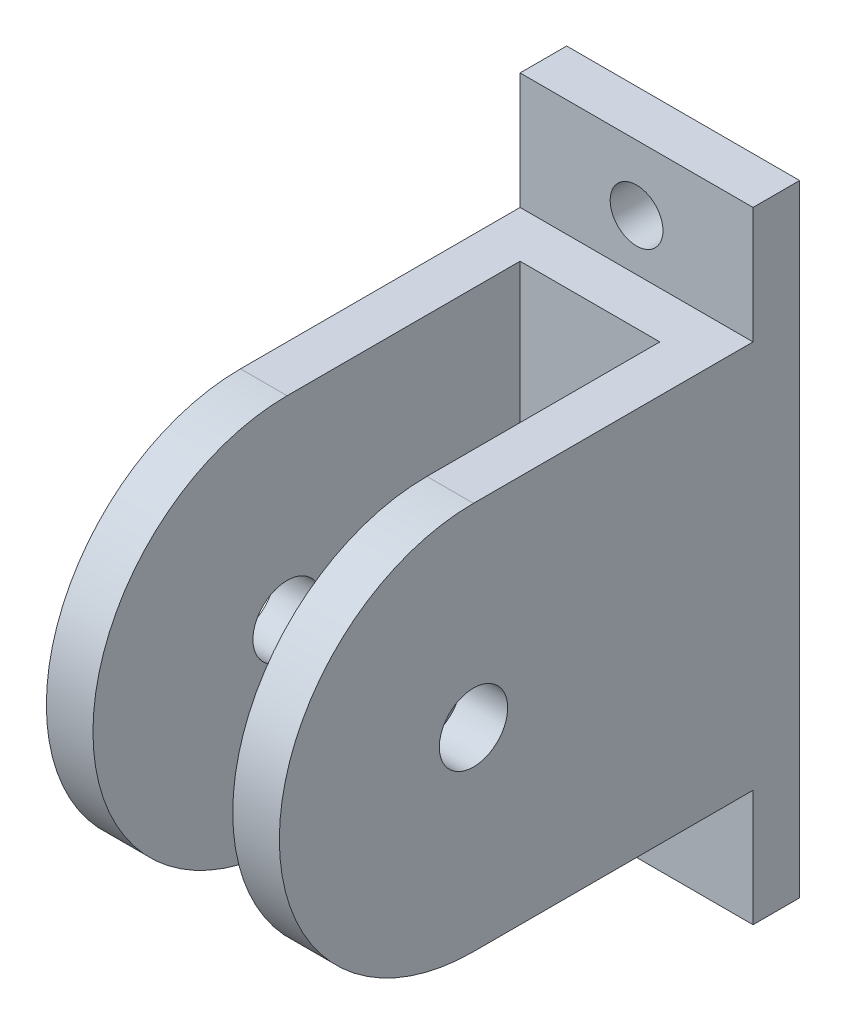
SolidWorks part; units mm, degrees
ref_plane "Piano frontale" through (0, 0, 0) normal (0, 0, 1) x (1, 0, 0)
ref_plane "Piano superiore" through (0, 0, 0) normal (0, 1, 0) x (1, 0, 0)
ref_plane "Piano destro" through (0, 0, 0) normal (1, 0, 0) x (0, 0, -1)
sketch "Schizzo1" plane through (0, 0, 0) normal (0, 0, 1) x (1, 0, 0)
  line L1 (-10, 20) -> (5, 20)
  line L2 (-10, 20) -> (-10, -20)
  line L3 (-10, -20) -> (5, -20)
  line L4 (5, 20) -> (5, -20)
  dimension "D1" = 40
  dimension "D2" = 15
extrude "Estrusione-Estrusione1" add sketch "Schizzo1" along normal blind 3
sketch "Schizzo2" plane through (0, 0, 3) normal (0, 0, 1) x (1, 0, 0)
  line L1 (-10, 12.5) -> (5, 12.5)
  line L2 (-10, 12.5) -> (-10, -12.5)
  line L3 (-10, -12.5) -> (5, -12.5)
  line L4 (5, 12.5) -> (5, -12.5)
  dimension "D1" = 25
  dimension "D2" = 15
extrude "Estrusione-Estrusione2" add sketch "Schizzo2" along normal blind 3
sketch "Schizzo5" plane through (-10, 0, 0) normal (-1, 0, 0) x (0, 0, 1)
  line L0 (6, 12.5) -> (21, 12.5)
  line L1 (6, 12.5) -> (6, -12.5)
  line L2 (6, -12.5) -> (21, -12.5)
  arc A0 (21, 12.5) -> (21, -12.5) centre (21, 0) cw
  point P7 (33.5, 0)
  dimension "D1" = 15
extrude "Estrusione-Estrusione4" add sketch "Schizzo5" against normal blind 3
sketch "Schizzo6" plane through (5, 0, 0) normal (1, 0, 0) x (0, 0, -1)
  line L0 (-6, -12.5) -> (-6, 12.5)
  line L1 (-6, 12.5) -> (-21, 12.5)
  line L2 (-6, -12.5) -> (-21, -12.5)
  arc A0 (-21, 12.5) -> (-21, -12.5) centre (-21, 0) ccw
extrude "Estrusione-Estrusione5" add sketch "Schizzo6" against normal blind 3
sketch "Schizzo7" plane through (-10, 0, 0) normal (-1, 0, 0) x (0, 0, 1)
  circle A0 centre (21, 0) radius 2.2
  point P0 (21, 0)
  dimension "D1" = 4.4
extrude "Taglio-Estrusione1" cut sketch "Schizzo7" against normal through all both and the other way through all
sketch "Schizzo9" plane through (0, 0, 0) normal (0, 0, -1) x (-1, 0, 0)
  line L0 (-5, 20) -> (10, 20) construction
  line L1 (-5, 0) -> (10, 0) construction
  line L2 (-5, -20) -> (-5, 20) construction
  line L3 (10, 20) -> (10, -20) construction
  circle A0 centre (2.5, 15.8) radius 1.7
  circle A1 centre (2.5, -15.8) radius 1.7
  point P2 (2.5, 20)
  dimension "D1" = 3.4
extrude "Taglio-Estrusione2" cut sketch "Schizzo9" against normal blind 7
